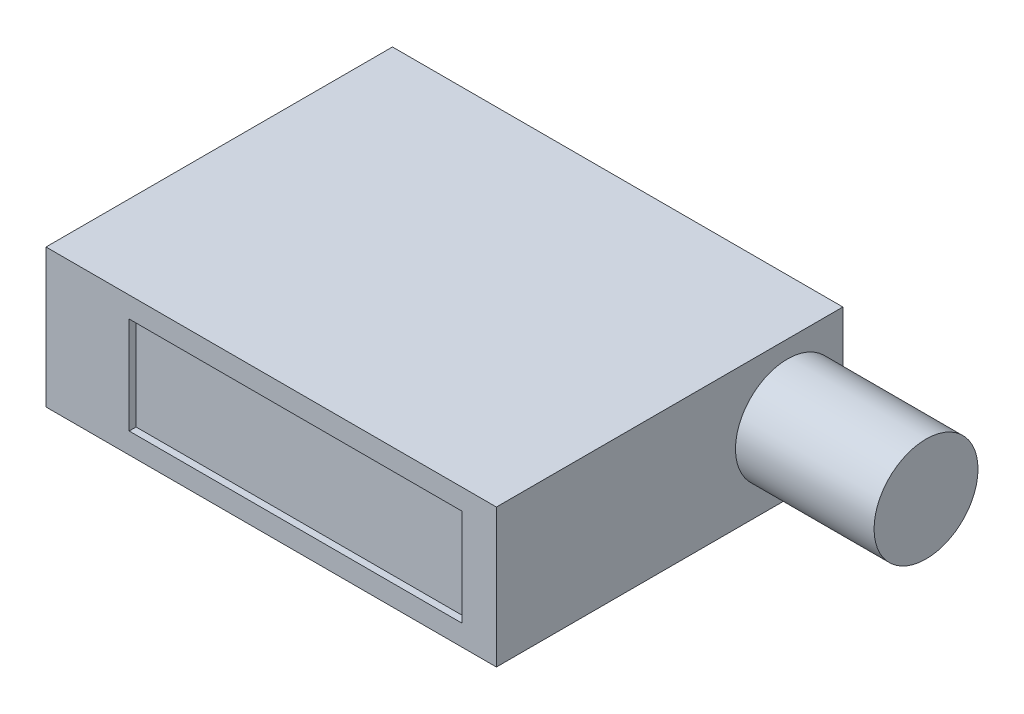
SolidWorks part; units mm, degrees
ref_plane "Front Plane" through (0, 0, 0) normal (0, 0, 1) x (1, 0, 0)
ref_plane "Top Plane" through (0, 0, 0) normal (0, 1, 0) x (1, 0, 0)
ref_plane "Right Plane" through (0, 0, 0) normal (1, 0, 0) x (0, 0, -1)
sketch "Sketch2" plane through (0, 0, 0) normal (0, 1, 0) x (1, 0, 0)
  line L1 (-32.5, 25) -> (32.5, 25)
  line L2 (-32.5, 25) -> (-32.5, -25)
  line L3 (-32.5, -25) -> (32.5, -25)
  line L4 (32.5, 25) -> (32.5, -25)
  line L5 (-32.5, 25) -> (32.5, -25) construction
  line L6 (-32.5, -25) -> (32.5, 25) construction
  point P0 (0, 0)
  dimension "D1" = 65
  dimension "D2" = 50
extrude "Boss-Extrude1" add sketch "Sketch2" along normal blind 20
sketch "Sketch4" plane through (0, 0, 25) normal (0, 0, 1) x (1, 0, 0)
  line L0 (-32.5, 10) -> (32.5, 10) construction
  line L1 (-32.5, 20) -> (-32.5, 0) construction
  line L2 (32.5, 20) -> (32.5, 0) construction
  line L4 (-20.5, 17) -> (27.5, 17)
  line L5 (-20.5, 17) -> (-20.5, 3)
  line L6 (-20.5, 3) -> (27.5, 3)
  line L7 (27.5, 17) -> (27.5, 3)
  line L8 (-20.5, 17) -> (27.5, 3) construction
  line L9 (-20.5, 3) -> (27.5, 17) construction
  point P6 (3.5, 10)
  dimension "D1" = 12
  dimension "D2" = 48
  dimension "D3" = 14
extrude "Cut-Extrude1" cut sketch "Sketch4" against normal blind 1
sketch "Sketch5" plane through (32.5, 0, 0) normal (1, 0, 0) x (0, 0, -1)
  line L0 (-25, 10) -> (25, 10) construction
  line L1 (-25, 20) -> (-25, 0) construction
  line L2 (25, 20) -> (25, 0) construction
  circle A0 centre (17, 10) radius 7.5
  dimension "D1" = 15
  dimension "D2" = 8
extrude "Boss-Extrude2" add sketch "Sketch5" along normal blind 20
